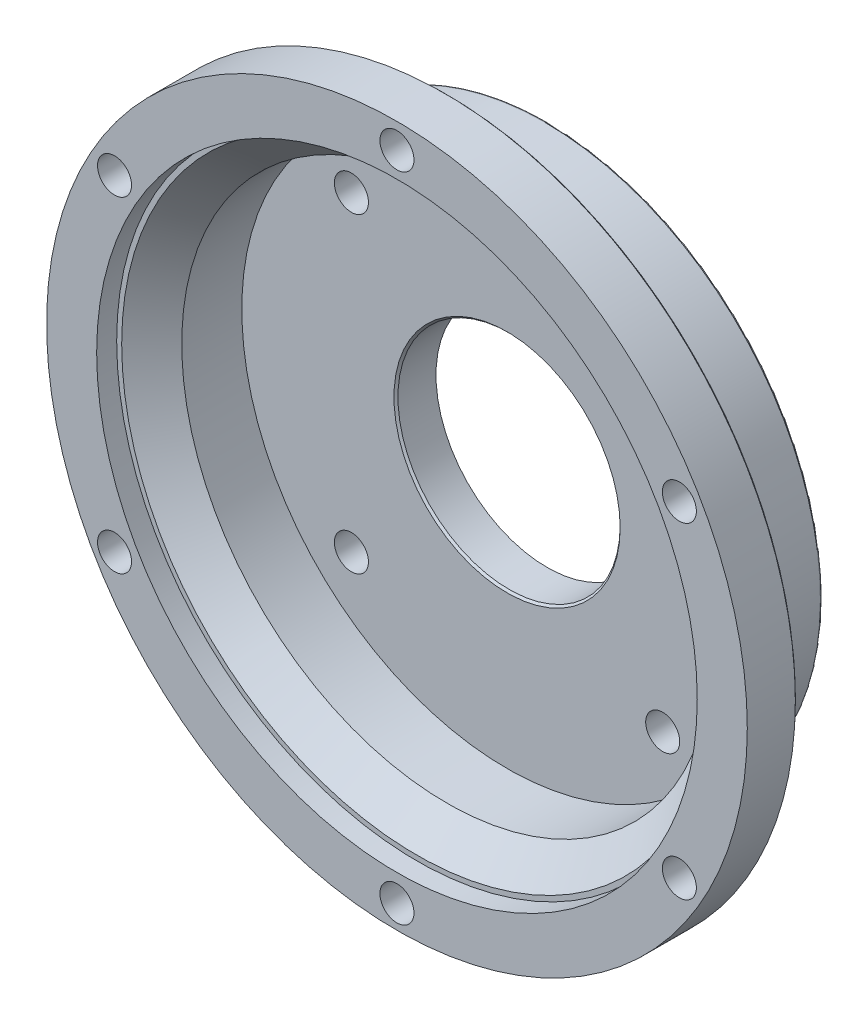
SolidWorks part; units mm, degrees
ref_plane "Front Plane" through (0, 0, 0) normal (0, 0, 1) x (1, 0, 0)
ref_plane "Top Plane" through (0, 0, 0) normal (0, 1, 0) x (1, 0, 0)
ref_plane "Right Plane" through (0, 0, 0) normal (1, 0, 0) x (0, 0, -1)
sketch "Sketch1" plane through (0, 0, 0) normal (0, 0, 1) x (1, 0, 0)
  circle A0 centre (0, 0) radius 35
  dimension "D1" = 70
extrude "Boss-Extrude1" add sketch "Sketch1" along normal blind 5 and the other way blind 10
sketch "Sketch2" plane through (0, 0, 5) normal (0, 0, 1) x (1, 0, 0)
  line L0 (0, 0) -> (0, 32.5)
  circle A0 centre (0, 0) radius 32.5
  point P4 (0, 32.5)
  dimension "D1" = 65
hole_wizard "M3 Clearance Hole1" positions "Sketch2" profile "Sketch3" hole size "M3" standard "ISO" end condition through all
sketch "Sketch3" plane through (0, 32.5, 5) normal (1, 0, 0) x (0, -1, 0)
  line L0 (0, 0) -> (0, 15)
  line L1 (0, 15) -> (1.7, 15)
  line L2 (1.7, 15) -> (1.7, 0)
  line L5 (1.7, 0) -> (0, 0)
  line L11 (0, -6.35) -> (0, 107.95) construction
  dimension "Thru Hole Dia." = 3.4
  dimension "Thru Hole Depth" = 15
pattern_circular "CirPattern1" count 6 over 360 about axis through (0, -0.0769, 0) along (0, 0, 1) of "M3 Clearance Hole1"
sketch "Sketch4" plane through (0, 0, 5) normal (0, 0, 1) x (1, 0, 0)
  circle A0 centre (0, 0) radius 30
  dimension "D1" = 60
extrude "Cut-Extrude1" cut sketch "Sketch4" against normal blind 2
sketch "Sketch5" plane through (0, 0, 3) normal (0, 0, 1) x (1, 0, 0)
  line L0 (0, -15.55) -> (0, 15.55)
  line L1 (-15.55, 15.55) -> (15.55, 15.55)
  line L2 (-15.55, -15.55) -> (15.55, -15.55)
  point P4 (0, 0)
  point P8 (0, 15.55)
  point P11 (0, -15.55)
  dimension "D1" = 31.1
  dimension "D2" = 31.1
  dimension "D3" = 31.1
hole_wizard "M3 Clearance Hole2" positions "3DSketch1" profile "Sketch7" hole size "M3" standard "ISO" end condition through all
sketch3d "3DSketch1"
  point P0 (-15.55, 15.55, 3)
  point P3 (15.55, 15.55, 3)
  point P6 (15.55, -15.55, 3)
  point P9 (-15.55, -15.55, 3)
sketch "Sketch7" plane through (-15.55, 15.55, 3) normal (1, 0, 0) x (0, -1, 0)
  line L0 (0, 0) -> (0, 13)
  line L1 (0, 13) -> (1.7, 13)
  line L2 (1.7, 13) -> (1.7, 0)
  line L5 (1.7, 0) -> (0, 0)
  line L11 (0, -6.35) -> (0, 107.95) construction
  dimension "Thru Hole Dia." = 3.4
  dimension "Thru Hole Depth" = 13
sketch "Sketch8" plane through (0, 0, -10) normal (0, 0, -1) x (-1, 0, 0)
  circle A0 centre (0, 0) radius 35
  circle A1 centre (0, 0) radius 27.5
  dimension "D1" = 55
extrude "Cut-Extrude4" cut sketch "Sketch8" against normal blind 4
fillet "Fillet1" radius 0.2 2 edges at (-35, 0, -6) (-27.5, 0, -10)
sketch "Sketch9" plane through (0, 0, 3) normal (0, 0, 1) x (1, 0, 0)
  line L0 (0, -15.55) -> (0, 15.55) construction
  circle A0 centre (0, 0) radius 11.1
  dimension "D1" = 22.2
extrude "Cut-Extrude5" cut sketch "Sketch9" against normal blind 10
sketch "Sketch10" plane through (0, 0, -10) normal (0, 0, -1) x (-1, 0, 0)
  line L0 (0, -15.55) -> (0, 15.55) construction
  circle A0 centre (0, 0) radius 27.5
  circle A1 centre (0, 0) radius 35
extrude "Cut-Extrude6" cut sketch "Sketch10" against normal blind 10
sketch "Sketch11" plane through (0, 0, 3) normal (0, 0, 1) x (1, 0, 0)
  circle A0 centre (0, 0) radius 26.5
  dimension "D1" = 53
extrude "Cut-Extrude7" cut sketch "Sketch11" against normal blind 9
sketch "Sketch12" plane through (0, 0, -7) normal (0, 0, 1) x (1, 0, 0)
  circle A0 centre (0, 0) radius 11.1
extrude "Cut-Extrude8" cut sketch "Sketch12" against normal blind 9
chamfer "Chamfer1" distance 0.2 angle 45 2 edges at (11.1, 0, -6) (-35, 0, 0)
chamfer "Chamfer2" distance 3 angle 45 1 edges at (26.5, 0, 3)
